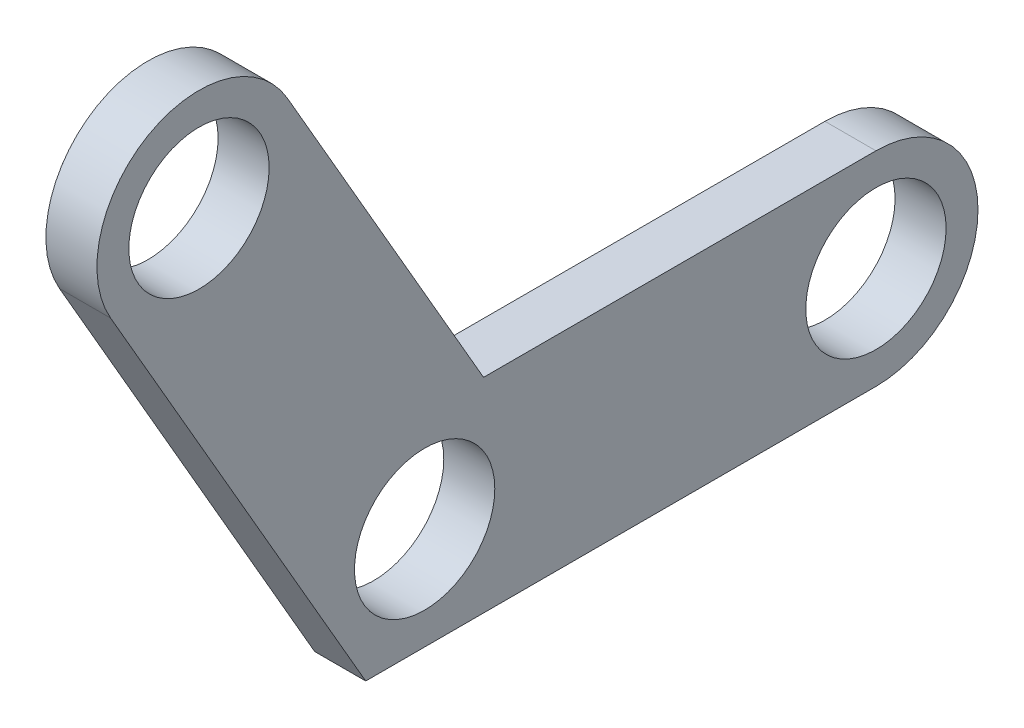
SolidWorks part; units mm, degrees
ref_plane "Front Plane" through (0, 0, 0) normal (0, 0, 1) x (1, 0, 0)
ref_plane "Top Plane" through (0, 0, 0) normal (0, 1, 0) x (1, 0, 0)
ref_plane "Right Plane" through (0, 0, 0) normal (1, 0, 0) x (0, 0, -1)
sketch "Sketch1" plane through (0, 0, 0) normal (1, 0, 0) x (0, 0, -1)
  line L0 (0, 0) -> (-10, 17.3205)
  line L1 (0, 0) -> (20, 0)
  line L3 (4.6188, 8) -> (20, 8)
  line L6 (-3.0718, 21.3205) -> (4.6188, 8)
  line L8 (4.6188, 8) -> (0, 0) construction
  circle A0 centre (-6.5359, 19.3205) radius 2.75
  circle A1 centre (20, 4) radius 2.75
  circle A2 centre (2.3094, 4) radius 2.75
  arc A3 (-3.0718, 21.3205) -> (-10, 17.3205) centre (-6.5359, 19.3205) ccw
  arc A4 (20, 0) -> (20, 8) centre (20, 4) ccw
  dimension "D1" = 5.5
  dimension "D5" = 20
  dimension "D7" = 5.5
  dimension "D8" = 4
  dimension "D10" = 5.5
  dimension "D6" = 4
  dimension "D2" = 8
  dimension "D3" = 8
  dimension "D4" = 20
  dimension "D11" = 4
  dimension "D12" = 120
extrude "Boss-Extrude1" add sketch "Sketch1" along normal blind 2
